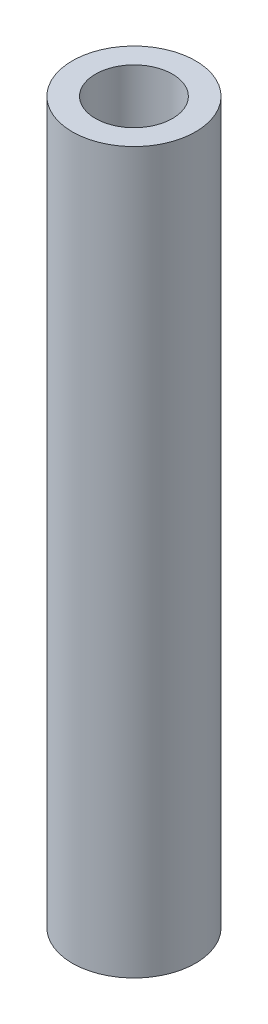
SolidWorks part; units mm, degrees
ref_plane "前视基准面" through (0, 0, 0) normal (0, 0, 1) x (1, 0, 0)
ref_plane "上视基准面" through (0, 0, 0) normal (0, 1, 0) x (1, 0, 0)
ref_plane "右视基准面" through (0, 0, 0) normal (1, 0, 0) x (0, 0, -1)
other "Configuration Table"
sketch "草图1" plane through (0, 0, 0) normal (0, 1, 0) x (1, 0, 0)
  circle A0 centre (0, 0) radius 2.5
  circle A1 centre (0, 0) radius 4
  dimension "D1" = 5
  dimension "D2" = 8
extrude "凸台-拉伸1" add sketch "草图1" along normal blind 46.75
